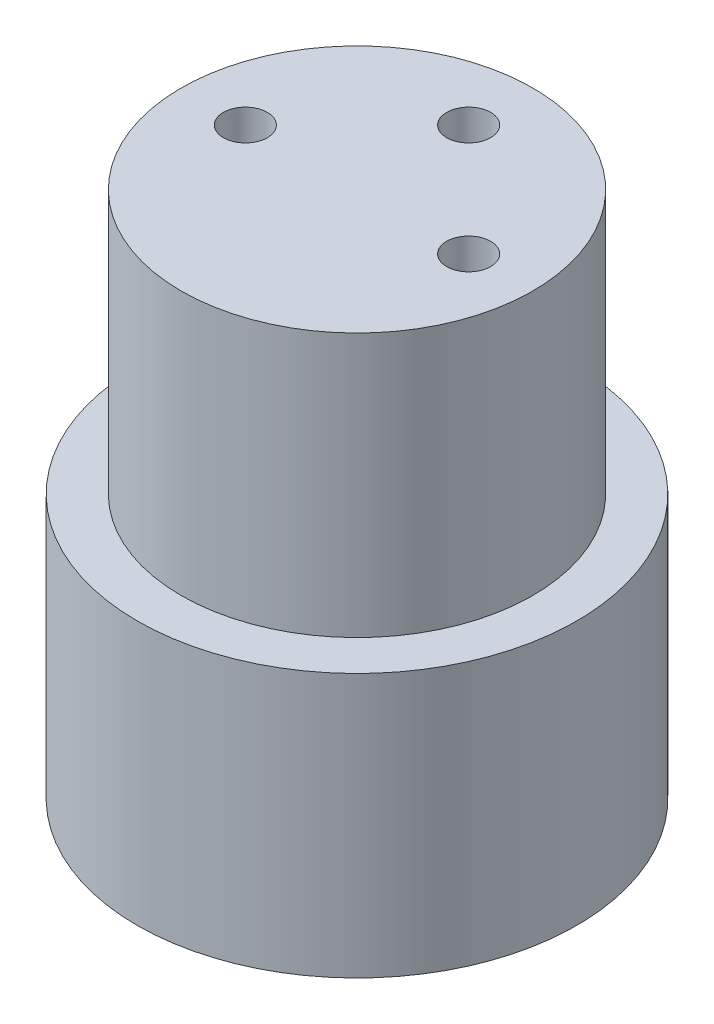
SolidWorks part; units mm, degrees
ref_plane "Спереди" through (0, 0, 0) normal (0, 0, 1) x (1, 0, 0)
ref_plane "Сверху" through (0, 0, 0) normal (0, 1, 0) x (1, 0, 0)
ref_plane "Справа" through (0, 0, 0) normal (1, 0, 0) x (0, 0, -1)
sketch "Эскиз1" plane through (0, 0, 0) normal (0, 1, 0) x (1, 0, 0)
  circle A0 centre (0, 0) radius 2.5
extrude "Бобышка-Вытянуть1" add sketch "Эскиз1" along normal blind 3
sketch "Эскиз2" plane through (0, 3, 0) normal (0, 1, 0) x (1, 0, 0)
  circle A0 centre (0, 0) radius 2
extrude "Бобышка-Вытянуть2" add sketch "Эскиз2" along normal blind 3
sketch "Эскиз3" plane through (0, 0, 0) normal (0, -1, 0) x (1, 0, 0)
  circle A1 centre (0, -1.27) radius 0.25
  circle A2 centre (1.27, 0) radius 0.25
  circle A3 centre (-1.27, 0) radius 0.25
extrude "Вырез-Вытянуть1" cut sketch "Эскиз3" against normal blind 10
